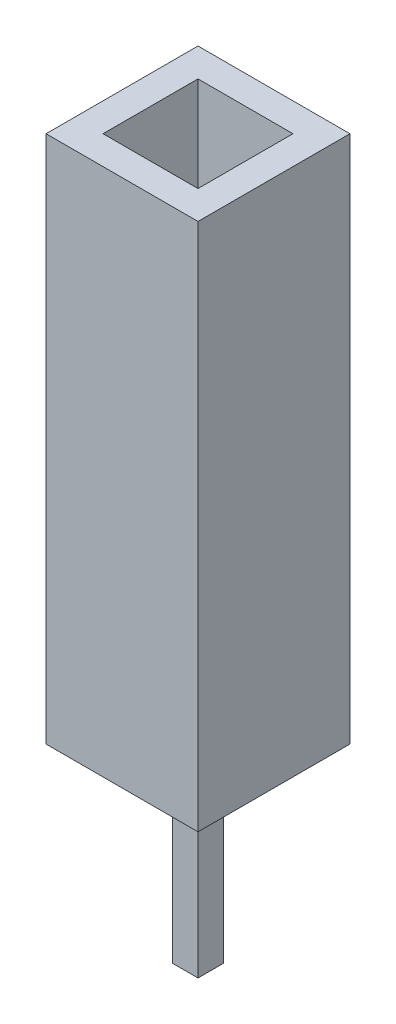
SolidWorks part; units mm, degrees
ref_plane "Front Plane" through (0, 0, 0) normal (0, 0, 1) x (1, 0, 0)
ref_plane "Top Plane" through (0, 0, 0) normal (0, 1, 0) x (1, 0, 0)
ref_plane "Right Plane" through (0, 0, 0) normal (1, 0, 0) x (0, 0, -1)
sketch "Sketch1" plane through (0, 0, 0) normal (0, 1, 0) x (1, 0, 0)
  line L1 (1.2, 1.2) -> (-1.2, 1.2)
  line L2 (1.2, 1.2) -> (1.2, -1.2)
  line L3 (1.2, -1.2) -> (-1.2, -1.2)
  line L4 (-1.2, 1.2) -> (-1.2, -1.2)
  line L5 (1.2, 1.2) -> (-1.2, -1.2) construction
  line L6 (1.2, -1.2) -> (-1.2, 1.2) construction
  point P0 (0, 0)
  dimension "D1" = 2.4
  dimension "D2" = 2.4
extrude "Boss-Extrude1" add sketch "Sketch1" along normal blind 8.35
sketch "Sketch2" plane through (0, 8.35, 0) normal (0, 1, 0) x (1, 0, 0)
  line L1 (-0.75, -0.75) -> (0.75, -0.75)
  line L2 (-0.75, -0.75) -> (-0.75, 0.75)
  line L3 (-0.75, 0.75) -> (0.75, 0.75)
  line L4 (0.75, -0.75) -> (0.75, 0.75)
  line L5 (-0.75, -0.75) -> (0.75, 0.75) construction
  line L6 (-0.75, 0.75) -> (0.75, -0.75) construction
  point P0 (0, 0)
  dimension "D1" = 1.5
  dimension "D2" = 1.5
extrude "Cut-Extrude1" cut sketch "Sketch2" against normal blind 8
sketch "Sketch3" plane through (0, 0, 0) normal (0, -1, 0) x (1, 0, 0)
  line L1 (-0.2, 0.2) -> (0.2, 0.2)
  line L2 (-0.2, 0.2) -> (-0.2, -0.2)
  line L3 (-0.2, -0.2) -> (0.2, -0.2)
  line L4 (0.2, 0.2) -> (0.2, -0.2)
  line L5 (-0.2, 0.2) -> (0.2, -0.2) construction
  line L6 (-0.2, -0.2) -> (0.2, 0.2) construction
  point P0 (0, 0)
  dimension "D1" = 0.4
  dimension "D2" = 0.4
extrude "Boss-Extrude2" add sketch "Sketch3" along normal blind 3
sketch "Sketch4" plane through (0, -3, 0) normal (0, -1, 0) x (1, 0, 0)
  line L0 (0.2, 0.2) -> (-0.2, 0.2) construction
  circle A0 centre (0, 0) radius 0.2
